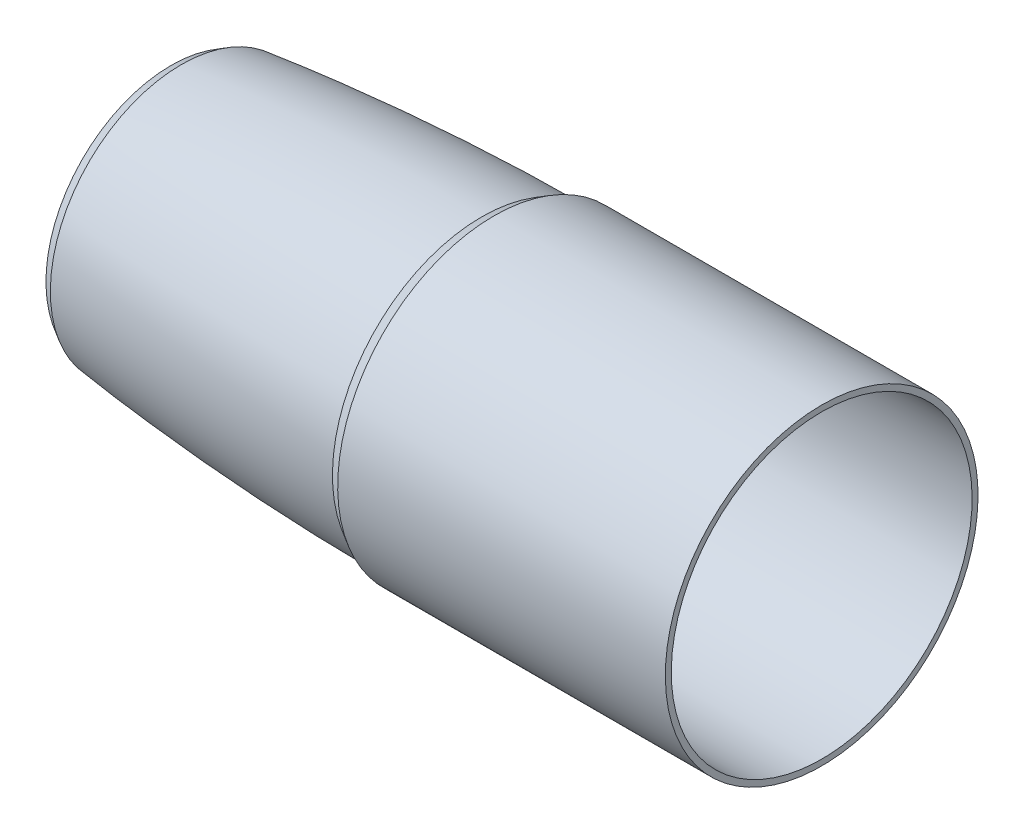
SolidWorks part; units mm, degrees
ref_plane "Front Plane" through (0, 0, 0) normal (0, 0, 1) x (1, 0, 0)
ref_plane "Top Plane" through (0, 0, 0) normal (0, 1, 0) x (1, 0, 0)
ref_plane "Right Plane" through (0, 0, 0) normal (1, 0, 0) x (0, 0, -1)
sketch "Sketch1" plane through (0, 0, 0) normal (0, 0, 1) x (1, 0, 0)
  line L0 (0, 0) -> (-229, 0) construction
  line L1 (0, 36.6) -> (0, -642.3338) construction
  line L3 (-229, 0) -> (-219.9054, 0)
  line L4 (83, 38.1) -> (2.5981, 38.1)
  line L7 (0, 39.6) -> (83, 39.6)
  line L8 (83, 38.1) -> (83, 39.6)
  line L9 (0, 36.6) -> (2.5981, 38.1)
  line L10 (0, 36.6) -> (119.7357, 36.6) construction
  line L11 (2.5981, 38.1) -> (119.7357, 38.1) construction
  line L12 (119.7357, 36.6) -> (119.7357, 38.1) construction
  line L13 (-79.2, 81.783) -> (-79.2, 33.1729) construction
  line L15 (0, 39.6) -> (-3.1302, 37.7928)
  line L16 (-79.2, 33.1729) -> (-81.8386, 31.6495)
  line L17 (-79.2, 31.9647) -> (-79.2, -62.4632) construction
  circle A0 centre (0, -642.3338) radius 681.9338 construction
  arc A1 (-229, 0) -> (0, 39.6) centre (0, -642.3338) cw
  arc A2 (-219.9054, 0) -> (0, 36.6) centre (0, -642.3338) cw
  arc A3 (-227.9926, -2.8258) -> (0, 36.6) centre (0, -642.3338) cw construction
  arc A4 (-79.2, 33.1729) -> (-3.1302, 37.7928) centre (0, -642.3338) cw
  arc A5 (-220.2941, 1.1353) -> (0, 37.8) centre (0, -642.3338) cw construction
  point P0 (0, 39.6)
  dimension "D1" = 39.6
  dimension "D2" = 229
  dimension "D3" = 681.9338
  dimension "D5" = 83
  dimension "D6" = 1.5
  dimension "D7" = 30
  dimension "D8" = 80.4019
  dimension "D9" = 1.5
  dimension "D10" = 38.1
  dimension "D11" = 1.2
  dimension "D12" = 79.2
  dimension "D13" = 30
  dimension "D14" = 30
  dimension "D4" = 3
revolve "Revolve1" add sketch "Sketch1" angle 360 about L0
